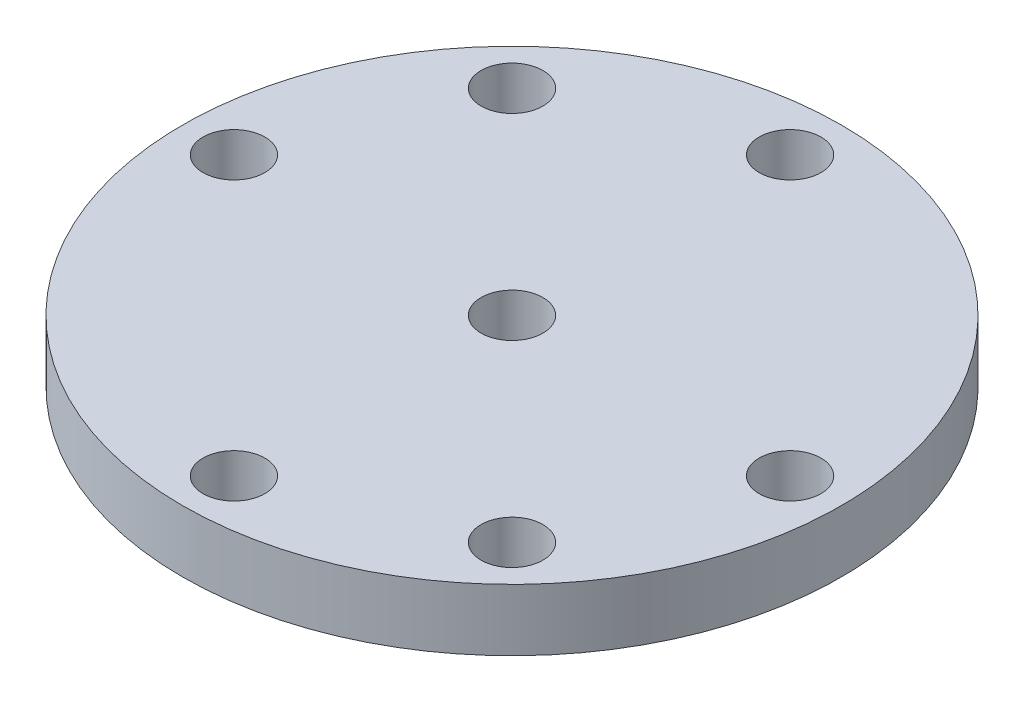
SolidWorks part; units mm, degrees
ref_plane "Plano frontal" through (0, 0, 0) normal (0, 0, 1) x (1, 0, 0)
ref_plane "Plano superior" through (0, 0, 0) normal (0, 1, 0) x (1, 0, 0)
ref_plane "Plano direito" through (0, 0, 0) normal (1, 0, 0) x (0, 0, -1)
sketch "Esboço1" plane through (0, 0, 0) normal (0, 1, 0) x (1, 0, 0)
  circle A0 centre (0, 0) radius 32
  circle A1 centre (0, 0) radius 5
  circle A2 centre (0, 27) radius 3
  circle A5 centre (27, 0) radius 3
  circle A6 centre (0, -27) radius 3
  circle A7 centre (-27, 0) radius 3
  circle A8 centre (-19.0919, 19.0919) radius 3
  circle A9 centre (19.0919, -19.0919) radius 3
  point P15 (0, 0)
  dimension "D2" = 10
  dimension "D3" = 27
  dimension "D4" = 27
  dimension "D6" = 6
  dimension "D10" = 64
  dimension "D11" = 45
  dimension "D5" = 45
  dimension "D7" = 27
  dimension "D8" = 27
  dimension "D9" = 27
  dimension "D12" = 45
  dimension "D13" = 90
  dimension "D14" = 45
  dimension "D15" = 90
extrude "Ressalto-extrusão1" add sketch "Esboço1" along normal blind 6
sketch "Esboço2" plane through (0, 6, 0) normal (0, 1, 0) x (1, 0, 0)
  circle A0 centre (0, 0) radius 5
  circle A1 centre (0, 0) radius 5 construction
  circle A2 centre (0, 0) radius 3
  dimension "D1" = 6
extrude "Ressalto-extrusão3" add sketch "Esboço2" against normal blind 6 contours A0 | A2
